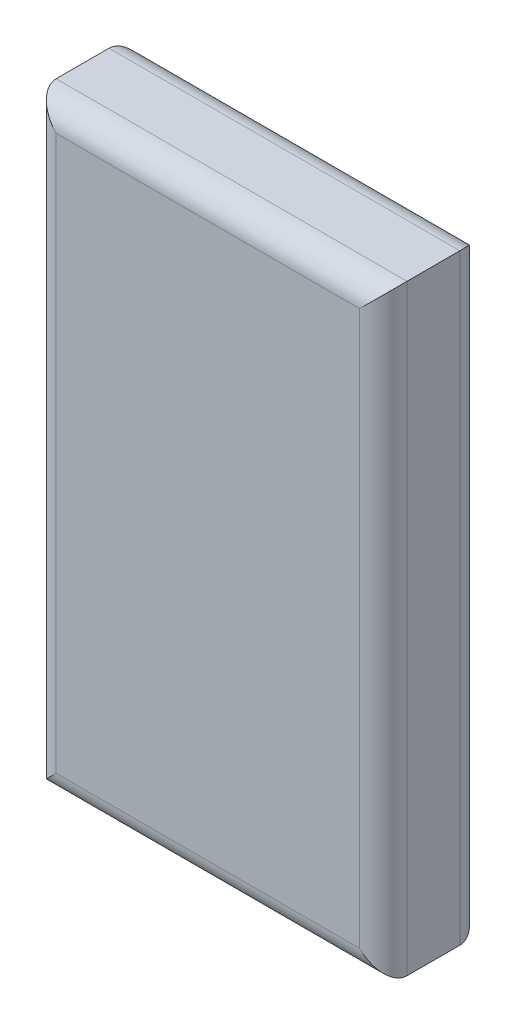
SolidWorks part; units mm, degrees
ref_plane "Front Plane" through (0, 0, 0) normal (0, 0, 1) x (1, 0, 0)
ref_plane "Top Plane" through (0, 0, 0) normal (0, 1, 0) x (1, 0, 0)
ref_plane "Right Plane" through (0, 0, 0) normal (1, 0, 0) x (0, 0, -1)
sketch "Sketch1" plane through (0, 0, 0) normal (0, 0, 1) x (1, 0, 0)
  line L1 (-11.1125, -19.05) -> (11.1125, -19.05)
  line L2 (-11.1125, -19.05) -> (-11.1125, 19.05)
  line L3 (-11.1125, 19.05) -> (11.1125, 19.05)
  line L4 (11.1125, -19.05) -> (11.1125, 19.05)
  line L5 (-11.1125, -19.05) -> (11.1125, 19.05) construction
  line L6 (-11.1125, 19.05) -> (11.1125, -19.05) construction
  point P0 (0, 0)
  dimension "D1" = 22.225
  dimension "D2" = 38.1
extrude "Boss-Extrude1" add sketch "Sketch1" along normal blind 6.35
fillet "Fillet1" radius 1.5 8 edges at (0, 19.05, 0) (-11.1125, 0, 0) (0, -19.05, 0) (11.1125, 0, 0) (0, -19.05, 6.35) (-11.1125, 0, 6.35) (0, 19.05, 6.35) (11.1125, 0, 6.35)
